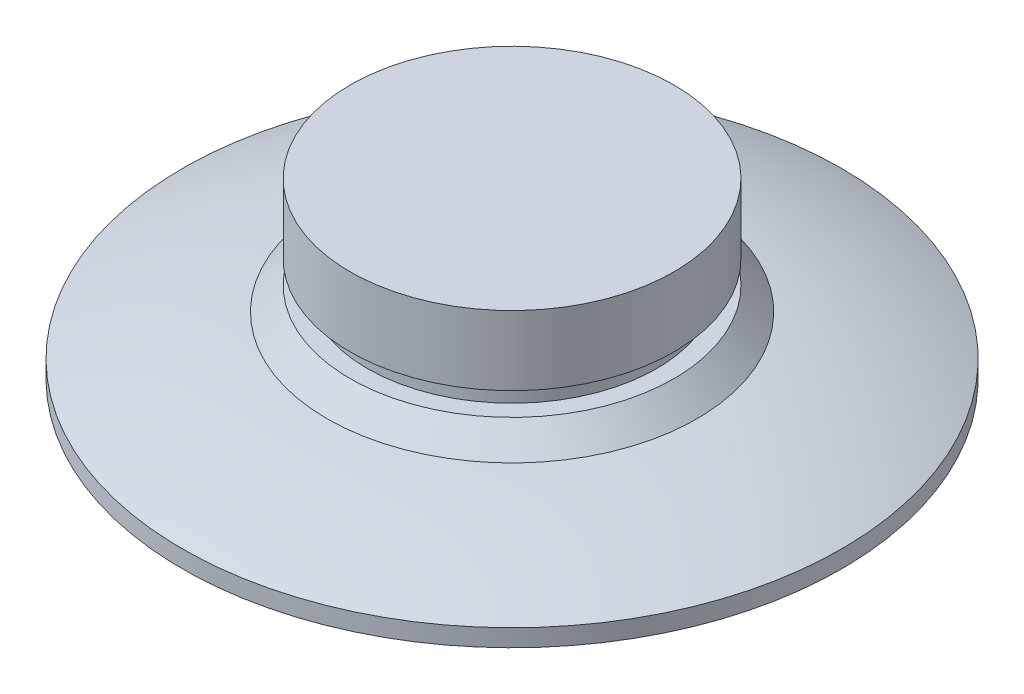
SolidWorks part; units mm, degrees
ref_plane "前视基准面" through (0, 0, 0) normal (0, 0, 1) x (1, 0, 0)
ref_plane "上视基准面" through (0, 0, 0) normal (0, 1, 0) x (1, 0, 0)
ref_plane "右视基准面" through (0, 0, 0) normal (1, 0, 0) x (0, 0, -1)
sketch "草图2" plane through (0, 0, 0) normal (0, 0, 1) x (1, 0, 0)
  line L0 (0, 0) -> (28.5, 0)
  line L1 (28.5, 0) -> (28.5, 1.5)
  line L2 (0, -10.7868) -> (0, 16.9055) construction
  line L3 (0, 15) -> (14, 15)
  line L4 (-8.565, 5) -> (24.1943, 5) construction
  line L5 (14, 15) -> (14, 9)
  line L6 (14, 7) -> (16, 5)
  line L7 (0, 0) -> (0, 15)
  line L8 (14, 9) -> (12.5, 9)
  line L9 (12.5, 9) -> (12.5, 7)
  line L10 (12.5, 7) -> (14, 7)
  arc A0 (16, 5) -> (28.5, 1.5) centre (10.0887, -40.1834) cw
  dimension "D8" = 45.5684
  dimension "D1" = 28.5
  dimension "D2" = 1.5
  dimension "D3" = 14
  dimension "D4" = 15
  dimension "D5" = 5
  dimension "D6" = 8
  dimension "D7" = 16
  dimension "D9" = 6
  dimension "D10" = 1.5
revolve "旋转1" add sketch "草图2" angle 360 about L7
